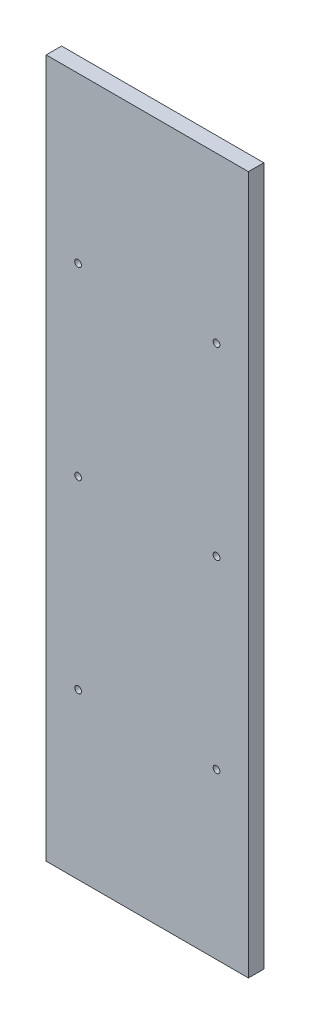
SolidWorks part; units mm, degrees
ref_plane "Front Plane" through (0, 0, 0) normal (0, 0, 1) x (1, 0, 0)
ref_plane "Top Plane" through (0, 0, 0) normal (0, 1, 0) x (1, 0, 0)
ref_plane "Right Plane" through (0, 0, 0) normal (1, 0, 0) x (0, 0, -1)
sketch "Sketch1" plane through (0, 0, 0) normal (0, 0, 1) x (1, 0, 0)
  line B0 (83.5, 0) -> (0, 0)
  line B1 (0, 0) -> (0, -288.29)
  line B2 (0, -288.29) -> (83.5, -288.29)
  line B3 (83.5, -288.29) -> (83.5, 0)
  circle B4 centre (13.175, -220.345) radius 1.3891
  circle B5 centre (70.325, -220.345) radius 1.3891
  circle B6 centre (70.325, -144.145) radius 1.3891
  circle B7 centre (13.175, -67.945) radius 1.3891
  circle B8 centre (70.325, -67.945) radius 1.3891
  circle B9 centre (13.175, -144.145) radius 1.3891
sketch_block_instance "Top-1"
sketch_block "Top"
extrude "Boss-Extrude1" add sketch "Sketch1" along normal blind 6.35
